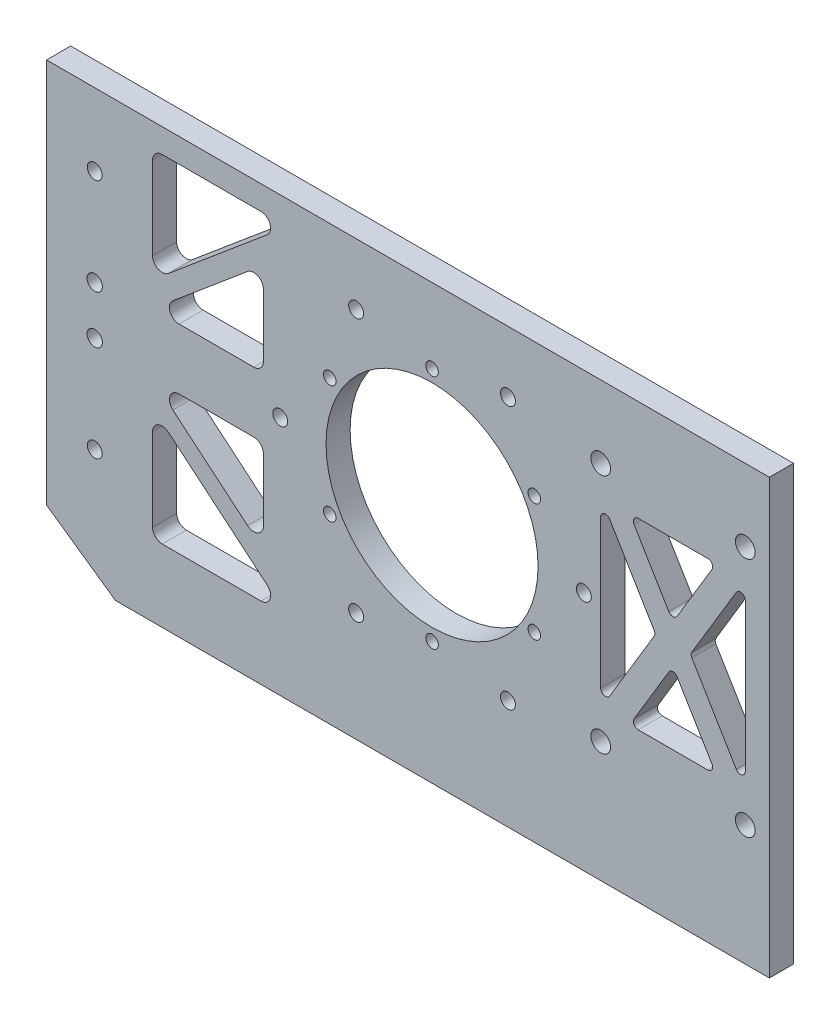
SolidWorks part; units mm, degrees
ref_plane "前视基准面" through (0, 0, 0) normal (0, 0, 1) x (1, 0, 0)
ref_plane "上视基准面" through (0, 0, 0) normal (0, 1, 0) x (1, 0, 0)
ref_plane "右视基准面" through (0, 0, 0) normal (1, 0, 0) x (0, 0, -1)
sketch "草图1" plane through (0, 0, 0) normal (0, 0, 1) x (1, 0, 0)
  line L1 (-80, 40) -> (70, 40)
  line L2 (-80, 40) -> (-80, -40)
  line L3 (-80, -40) -> (70, -40)
  line L4 (70, 40) -> (70, -40)
  circle A0 centre (0, 0) radius 24.5 construction
  circle A1 centre (0, -24.5) radius 1.3
  circle A2 centre (-21.2176, -12.25) radius 1.3
  circle A3 centre (-21.2176, 12.25) radius 1.3
  circle A4 centre (0, 0) radius 22
  circle A5 centre (0, 24.5) radius 1.3
  circle A6 centre (21.2176, 12.25) radius 1.3
  circle A7 centre (21.2176, -12.25) radius 1.3
  point P11 (0, 0)
  point P15 (70, 0)
  dimension "D1" = 49
  dimension "D2" = 2.6
  dimension "D4" = 44
  dimension "D5" = 80
  dimension "D6" = 70
  dimension "D7" = 80
  dimension "D3" = 6
extrude "凸台-拉伸1" add sketch "草图1" along normal blind 5
sketch "草图3" plane through (0, 0, 5) normal (0, 0, 1) x (1, 0, 0)
  line L0 (0, 0) -> (-70, 0) construction
  line L1 (-70, 0) -> (-70, -25) construction
  line L3 (-70, 0) -> (-70, 24.3133)
  circle A4 centre (-70, -25) radius 1.55
  circle A5 centre (-70, -5) radius 1.5828
  circle A6 centre (-70, 25) radius 1.55
  circle A7 centre (-70, 5) radius 1.5828
  point P6 (-70, 0)
  dimension "D3" = 3.1
  dimension "D4" = 20
  dimension "D1" = 70
  dimension "D2" = 25
extrude "切除-拉伸3" cut sketch "草图3" against normal blind 12.5
sketch "草图4" plane through (0, 0, 5) normal (0, 0, 1) x (1, 0, 0)
  line L0 (-58, 35) -> (-30, 35)
  line L1 (-30, 35) -> (-58, 11.5052)
  line L2 (-58, 11.5052) -> (-58, 35)
  line L3 (-35, 25.5829) -> (-58, 6.2836)
  line L4 (-58, 6.2836) -> (-35, 6.2836)
  line L5 (-35, 6.2836) -> (-35, 25.5829)
  line L8 (70, 40) -> (-80, 40) construction
  line L9 (-80, 40) -> (-80, -40) construction
  dimension "D1" = 5
  dimension "D2" = 22
  dimension "D3" = 140
  dimension "D4" = 45
  dimension "D6" = 4
extrude "切除-拉伸5" cut sketch "草图4" against normal blind 8 contours L2 L0 L1 | L5 L3 L4
fillet "圆角3" radius 2 6 edges at (-35, 6.2836, 2.5) (-58, 6.2836, 2.5) (-35, 25.5829, 2.5) (-30, 35, 2.5) (-58, 11.5052, 2.5) (-58, 35, 2.5)
mirror "镜向2" about plane through (0, 0, 0) normal (0, 1, 0) of "圆角3", "切除-拉伸5"
sketch "草图10" plane through (0, 0, 5) normal (0, 0, 1) x (1, 0, 0)
  line L0 (-80, -40) -> (-127.0531, -7.0531)
  line L1 (-127.0531, -7.0531) -> (-80, 40)
  line L2 (-80, -40) -> (70, -40) construction
  line L3 (-80, 40) -> (-80, -40) construction
  line L4 (-80, 40) -> (-80, -40)
  dimension "D1" = 145
  dimension "D2" = 45
extrude "凸台-拉伸4" add sketch "草图10" against normal up to surface (5 mm away) contours L4 L0 L1 up to face at (-49.3474, 27.3903, 0)
fillet "圆角5" radius 5 1 edges at (-127.0531, -7.0531, 2.5)
sketch "草图11" plane through (0, 0, 5) normal (0, 0, 1) x (1, 0, 0)
  line L0 (0, 0) -> (0, 34) construction
  line L1 (0, 0) -> (-15.75, 27.2798)
  circle A0 centre (0, 0) radius 29 construction
  circle A1 centre (0, 0) radius 34 construction
  circle A2 centre (0, 0) radius 31.5 construction
  circle A3 centre (-15.75, 27.2798) radius 1.55
  circle A4 centre (15.75, 27.2798) radius 1.55
  circle A5 centre (31.5, 0) radius 1.55
  circle A6 centre (15.75, -27.2798) radius 1.55
  circle A7 centre (-15.75, -27.2798) radius 1.55
  circle A8 centre (-31.5, 0) radius 1.55
  point P20 (0, 0)
  dimension "D1" = 58
  dimension "D2" = 68
  dimension "D3" = 63
  dimension "D5" = 3.1
  dimension "D4" = 30
  dimension "D6" = 6
extrude "切除-拉伸7" cut sketch "草图11" against normal blind 25 contours A3 | A4 | A5 | A6 | A7 | A8
sketch "草图12" plane through (0, 0, 5) normal (0, 0, 1) x (1, 0, 0)
  line L0 (0, 0) -> (50, 0) construction
  line L6 (35, -25) -> (65, -25) construction
  line L7 (35, -25) -> (35, 25) construction
  line L8 (35, 25) -> (65, 25) construction
  line L9 (65, -25) -> (65, 25) construction
  line L10 (35, -25) -> (65, 25) construction
  line L11 (35, 25) -> (65, -25) construction
  circle A0 centre (0, 0) radius 28 construction
  circle A1 centre (35, 25) radius 2.05
  circle A2 centre (65, 25) radius 2.05
  circle A3 centre (65, -25) radius 2.05
  circle A4 centre (35, -25) radius 2.05
  dimension "D3" = 56
  dimension "D5" = 4.1
  dimension "D6" = 4.1
  dimension "D1" = 30
  dimension "D2" = 50
  dimension "D4" = 50
extrude "切除-拉伸8" cut sketch "草图12" against normal blind 10
sketch "草图13" plane through (0, 0, 5) normal (0, 0, 1) x (1, 0, 0)
  line L0 (35, 25) -> (65, -25) construction
  line L6 (35, 25) -> (65, -25) construction
  line L10 (35, 19) -> (35, -19)
  line L11 (35, -19) -> (46.4, 0)
  line L12 (46.4, 0) -> (35, 19)
  line L13 (35, -25) -> (65, 25) construction
  line L14 (50, 0) -> (50, -49.4768) construction
  line L15 (65, -19) -> (53.6, 0)
  line L16 (65, 19) -> (65, -19)
  line L17 (53.6, 0) -> (65, 19)
  line L18 (41, 19) -> (50, 4)
  line L19 (50, 4) -> (59, 19)
  line L20 (59, 19) -> (41, 19)
  line L21 (35, 19) -> (65, 19) construction
  line L22 (50, 0) -> (90.4004, 0) construction
  line L23 (50, -4) -> (59, -19)
  line L24 (41, -19) -> (50, -4)
  line L25 (59, -19) -> (41, -19)
  circle A0 centre (35, -25) radius 2.05 construction
  circle A1 centre (65, 25) radius 2.05 construction
  point P4 (50, 0)
  dimension "D1" = 6
  dimension "D2" = 6
  dimension "D3" = 6
  dimension "D4" = 6
  dimension "D5" = 0
extrude "切除-拉伸9" cut sketch "草图13" against normal blind 10
fillet "圆角6" radius 1 12 edges at (35, -19, 2.5) (46.4, 0, 2.5) (35, 19, 2.5) (41, -19, 2.5) (50, -4, 2.5) (59, -19, 2.5) (65, -19, 2.5) (65, 19, 2.5) (53.6, 0, 2.5) (50, 4, 2.5) (59, 19, 2.5) (41, 19, 2.5)
sketch "草图14" plane through (0, 0, 5) normal (0, 0, 1) x (1, 0, 0)
  line L0 (-80, -40) -> (-65.7185, -50)
  line L1 (-65.7185, -50) -> (70, -50)
  line L2 (70, -50) -> (70, -40)
  line L3 (-80, -40) -> (-122.1719, -10.4709) construction
  line L4 (70, -40) -> (70, 40) construction
  line L5 (-80, -40) -> (70, -40) construction
  line L6 (-80, -40) -> (70, -40)
  dimension "D1" = 180
  dimension "D2" = 180
  dimension "D3" = 10
extrude "凸台-拉伸5" add sketch "草图14" against normal up to surface (5 mm away) contours L6 L0 L1 L2 up to face at (50, 13.974, 0)
sketch "草图16" plane through (0, 0, 0) normal (0, 0, -1) x (-1, 0, 0)
  circle A0 centre (0, 24.5) radius 2.25
  circle A1 centre (21.2176, 12.25) radius 2.25
  circle A2 centre (21.2176, -12.25) radius 2.25
  circle A3 centre (0, -24.5) radius 2.25
  circle A4 centre (-21.2176, -12.25) radius 2.25
  circle A5 centre (-21.2176, 12.25) radius 2.25
  point P15 (0, 0)
  dimension "D1" = 4.5
  dimension "D2" = 6
extrude "切除-拉伸10" cut sketch "草图16" against normal blind 2.5
sketch "草图17" plane through (0, 0, 5) normal (0, 0, 1) x (1, 0, 0)
  line L0 (50, -19) -> (50, 19) construction
  line L1 (42.7662, -19) -> (57.2338, -19) construction
  line L2 (57.2338, 19) -> (42.7662, 19) construction
  line L3 (50, 0) -> (-80, 0)
  line L4 (-80, 0) -> (-80, 40)
  line L5 (-122.8396, -2.8396) -> (-80, 40) construction
  line L6 (-122.8396, -2.8396) -> (-80, 40)
  line L7 (-65.7185, -50) -> (-122.1719, -10.4709) construction
  line L8 (-80, -40) -> (-122.1719, -10.4709)
  line L9 (-80, 0) -> (-80, -40)
  arc A0 (-122.8396, -2.8396) -> (-122.1719, -10.4709) centre (-119.3041, -6.3751) ccw construction
  arc A1 (-122.8396, -2.8396) -> (-122.1719, -10.4709) centre (-119.3041, -6.3751) ccw
  dimension "D1" = 130
extrude "切除-拉伸11" cut sketch "草图17" against normal blind 10 contours L6 A1 L8 L9 L4
